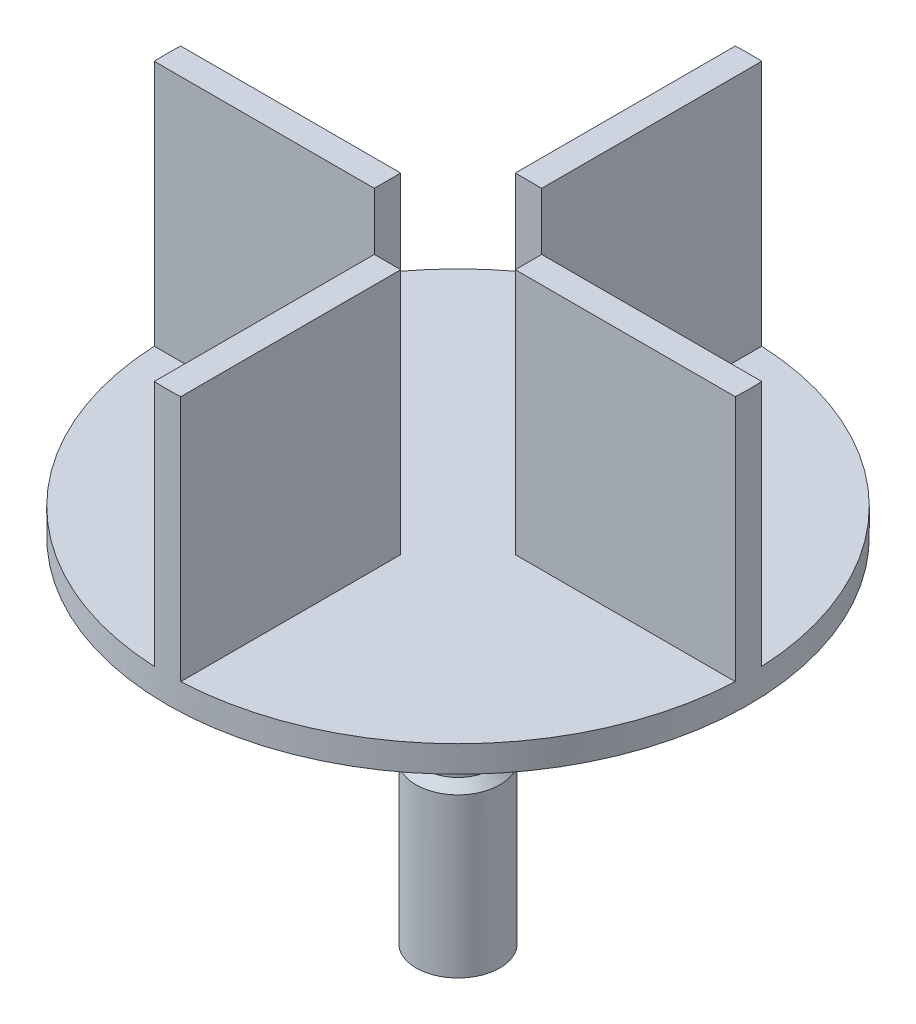
SolidWorks part; units mm, degrees
ref_plane "Front Plane" through (0, 0, 0) normal (0, 0, 1) x (1, 0, 0)
ref_plane "Top Plane" through (0, 0, 0) normal (0, 1, 0) x (1, 0, 0)
ref_plane "Right Plane" through (0, 0, 0) normal (1, 0, 0) x (0, 0, -1)
sketch "Sketch1" plane through (0, 0, 0) normal (0, 1, 0) x (1, 0, 0)
  circle A0 centre (0, 0) radius 33
  dimension "D1" = 66
extrude "Boss-Extrude1" add sketch "Sketch1" along normal blind 3
sketch "Sketch2" plane through (0, 3, 0) normal (0, 1, 0) x (1, 0, 0)
  line L0 (0, 33) -> (0, 8)
  line L1 (-1.5, 8) -> (1.5, 8)
  line L2 (1.5, 8) -> (1.5, 32.9659)
  line L3 (-1.5, 8) -> (-1.5, 32.9659)
  circle A0 centre (0, 0) radius 33 construction
  arc A1 (0, 33) -> (1.5, 32.9659) centre (0, 0) cw
  arc A2 (0, 33) -> (-1.5, 32.9659) centre (0, 0) ccw
  point P12 (0, 8)
  circle M2 centre (0, 0) radius 33
  dimension "D1" = 25
  dimension "D2" = 3
extrude "Boss-Extrude2" add sketch "Sketch2" along normal blind 28 contours L1 L2 L0 M2 | L3 L1 L0 M2
pattern_circular "CirPattern1" count 4 over 360 about axis through (0, 0, 0) along (0, 1, 0) of "Boss-Extrude2"
sketch "Sketch5" plane through (0, 0, 0) normal (0, -1, 0) x (1, 0, 0)
  circle A0 centre (0, 0) radius 4.75
  dimension "D1" = 9.5
extrude "Boss-Extrude3" add sketch "Sketch5" along normal blind 40
sketch "Sketch6" plane through (0, 0, 0) normal (0, 0, 1) x (1, 0, 0)
  line L0 (-4.75, -16) -> (-3.75, -17)
  line L1 (-4.75, 0) -> (-4.75, -40) construction
  line L2 (-3.75, -17) -> (-3.75, -21)
  line L3 (-3.75, -21) -> (-4.75, -22)
  line L4 (-4.75, -22) -> (-4.75, -16)
  line L5 (0, 0) -> (0, -40) construction
  line L6 (-4.75, -40) -> (4.75, -40) construction
  dimension "D1" = 45
  dimension "D2" = 6
  dimension "D3" = 22
  dimension "D4" = 1
revolve "Cut-Revolve1" cut sketch "Sketch6" angle 360 about L5
